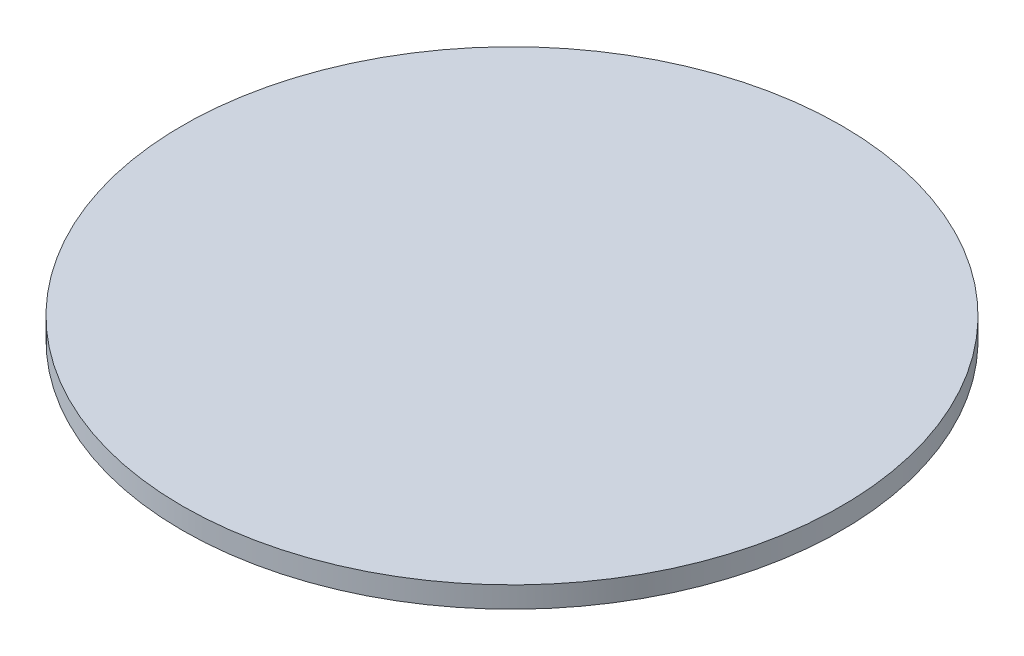
SolidWorks part; units mm, degrees
ref_plane "前视基准面" through (0, 0, 0) normal (0, 0, 1) x (1, 0, 0)
ref_plane "上视基准面" through (0, 0, 0) normal (0, 1, 0) x (1, 0, 0)
ref_plane "右视基准面" through (0, 0, 0) normal (1, 0, 0) x (0, 0, -1)
sketch "Sketch1" plane through (0, 0, 0) normal (0, 1, 0) x (1, 0, 0)
  circle A0 centre (0, 0) radius 25
  dimension "D1" = 50
extrude "Boss-Extrude1" add sketch "Sketch1" along normal blind 1.6
